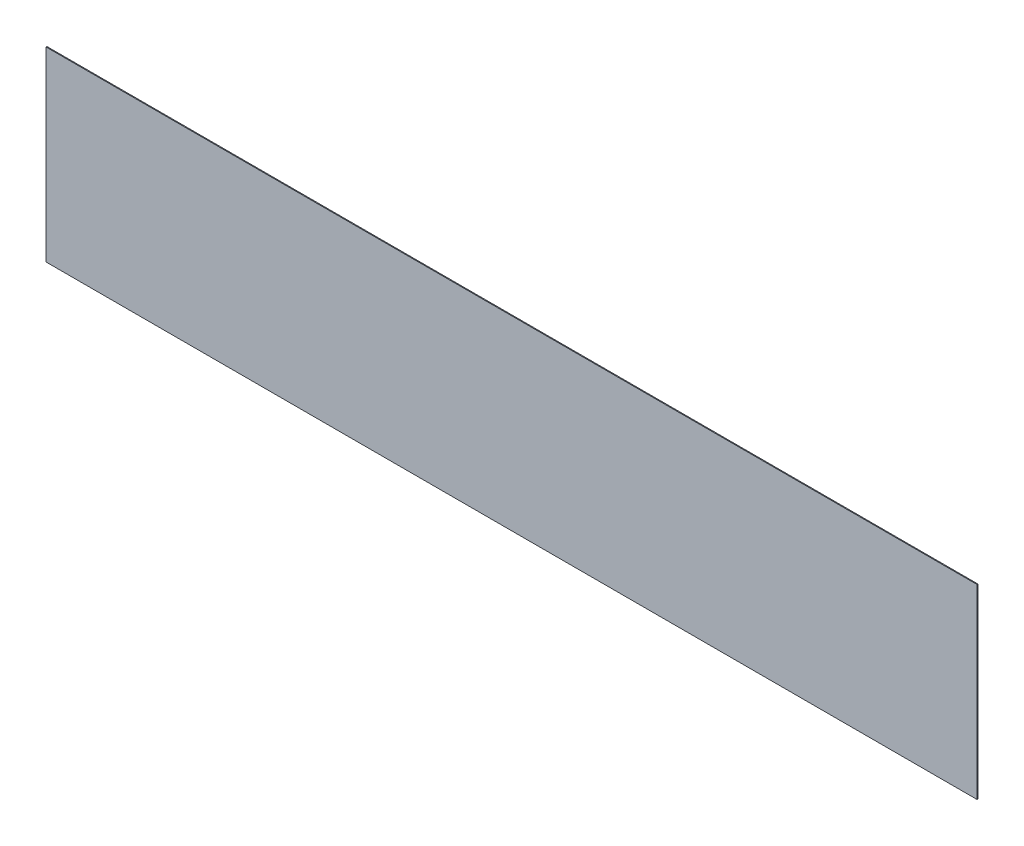
SolidWorks part; units mm, degrees
ref_plane "Front Plane" through (0, 0, 0) normal (0, 0, 1) x (1, 0, 0)
ref_plane "Top Plane" through (0, 0, 0) normal (0, 1, 0) x (1, 0, 0)
ref_plane "Right Plane" through (0, 0, 0) normal (1, 0, 0) x (0, 0, -1)
sketch "Sketch3" plane through (0, 0, 0) normal (0, 0, 1) x (1, 0, 0)
  line L0 (0, 16) -> (129.996, 16) construction
  line L1 (-20, -16) -> (0, -16) construction
  line L2 (-20, -16) -> (-20, 16) construction
  line L3 (-20, 16) -> (0, 16) construction
  line L4 (0, -16) -> (0, 16) construction
  line L6 (0, 16) -> (0, -16) construction
  line L8 (129.996, 16) -> (129.996, -16) construction
  line L10 (129.996, 16) -> (129.996, -16) construction
  line L13 (0, -16) -> (129.996, -16) construction
  line L14 (129.996, 16) -> (139.996, 16) construction
  line L15 (139.996, 16) -> (139.996, -16) construction
  line L16 (139.996, -16) -> (129.996, -16) construction
  line L17 (-20, 0) -> (139.996, 0) construction
  point P14 (0, 0)
ref_plane "FS y midplane" through (0, 0, 0) normal (0, -1, 0) x (1, 0, 0)
ref_plane "FS left edge" through (-20, 0, 0) normal (1, 0, 0) x (0, 1, 0)
ref_plane "FS right edge" through (139.996, 0, 0) normal (-1, 0, 0) x (0, -1, 0)
sketch "Sketch1" plane through (0, 0, 0) normal (0, 0, 1) x (1, 0, 0)
  line L10 (-20, 16) -> (-20, -16)
  line L11 (-20, -16) -> (139.996, -16)
  line L12 (139.996, -16) -> (139.996, 16)
  line L13 (139.996, 16) -> (-20, 16)
extrude "Boss-Extrude1" add sketch "Sketch1" along normal blind 0.15
sketch "Sketch2" plane through (0, 0, 0.15) normal (0, 0, 1) x (1, 0, 0)
  line L0 (0, 16) -> (129.996, 16) construction
  line L1 (-20, -13) -> (-6.5, -13)
  line L2 (-20, -13) -> (-20, -16)
  line L3 (-20, -16) -> (-6.5, -16)
  line L4 (-6.5, -13) -> (-6.5, -16)
  line L5 (-20, 0) -> (139.996, 0) construction
  line L11 (59.998, 16) -> (59.998, -16) construction
  line L14 (139.996, -16) -> (134.996, -16)
  line L15 (134.996, -11.8) -> (134.996, -16)
  line L16 (139.996, -11.8) -> (134.996, -11.8)
  line L17 (139.996, -11.8) -> (139.996, -16)
  line L18 (-20, -16) -> (-20, 16) construction
  line L19 (139.996, 16) -> (139.996, -16) construction
  line L20 (139.996, -16) -> (129.996, -16) construction
  line L21 (0, -16) -> (129.996, -16) construction
  point P13 (139.996, -13.9)
  point P34 (59.998, 0)
  dimension "D1" = 13.5
  dimension "D2" = 5
  dimension "D3" = 4.2
  dimension "D4" = 3
extrude "Cut-Extrude1" [suppressed] cut sketch "Sketch2" against normal through all
equation "\"D3@Sketch3\"=6*21.666"
